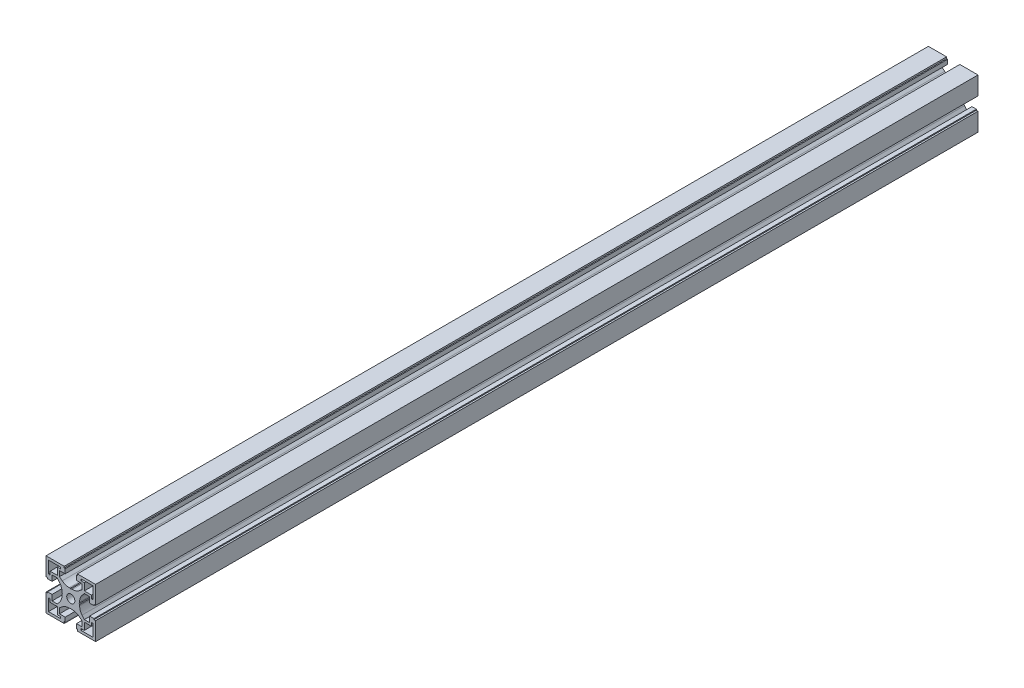
SolidWorks part; units mm, degrees
material "6061 Alloy"
ref_plane "Front Plane" through (0, 0, 0) normal (0, 0, 1) x (1, 0, 0)
ref_plane "Top Plane" through (0, 0, 0) normal (0, 1, 0) x (1, 0, 0)
ref_plane "Right Plane" through (0, 0, 0) normal (1, 0, 0) x (0, 0, -1)
sketch "Model" plane through (0, 0, 0) normal (0, 0, 1) x (1, 0, 0)
  line L0 (20.25, -9.25) -> (20.25, -20.25)
  line L1 (20.25, -9.25) -> (18.75, -9.25)
  line L2 (18.75, -9.25) -> (18.75, -12.25)
  line L3 (18.75, -12.25) -> (12.25, -12.25)
  line L4 (12.25, -12.25) -> (12.25, -18.75)
  line L5 (12.25, -18.75) -> (9.25, -18.75)
  line L6 (9.25, -18.75) -> (9.25, -20.25)
  line L7 (20.25, -20.25) -> (9.25, -20.25)
  line L8 (9.25, 20.25) -> (20.25, 20.25)
  line L9 (9.25, 20.25) -> (9.25, 18.75)
  line L10 (9.25, 18.75) -> (12.25, 18.75)
  line L11 (12.25, 18.75) -> (12.25, 12.25)
  line L12 (12.25, 12.25) -> (18.75, 12.25)
  line L13 (18.75, 12.25) -> (18.75, 9.25)
  line L14 (18.75, 9.25) -> (20.25, 9.25)
  line L15 (20.25, 20.25) -> (20.25, 9.25)
  line L16 (-9.25, -20.25) -> (-20.25, -20.25)
  line L17 (-9.25, -20.25) -> (-9.25, -18.75)
  line L18 (-9.25, -18.75) -> (-12.25, -18.75)
  line L19 (-12.25, -18.75) -> (-12.25, -12.25)
  line L20 (-12.25, -12.25) -> (-18.75, -12.25)
  line L21 (-18.75, -12.25) -> (-18.75, -9.25)
  line L22 (-18.75, -9.25) -> (-20.25, -9.25)
  line L23 (-20.25, -20.25) -> (-20.25, -9.25)
  line L24 (-20.25, 20.25) -> (-9.25, 20.25)
  line L25 (-20.25, 9.25) -> (-20.25, 20.25)
  line L26 (-20.25, 9.25) -> (-18.75, 9.25)
  line L27 (-18.75, 9.25) -> (-18.75, 12.25)
  line L28 (-18.75, 12.25) -> (-12.25, 12.25)
  line L29 (-12.25, 12.25) -> (-12.25, 18.75)
  line L30 (-12.25, 18.75) -> (-9.25, 18.75)
  line L31 (-9.25, 18.75) -> (-9.25, 20.25)
  line L32 (0.5, 8) -> (1.4727, 8)
  line L33 (7.7467, 10.213) -> (10.25, 12.2299)
  line L34 (10.25, 12.2299) -> (10.25, 17)
  line L35 (10.25, 17) -> (5.1, 17)
  line L36 (5.1, 17) -> (5.1, 21)
  line L37 (5.1, 21) -> (6, 21)
  line L38 (6, 22.5) -> (6, 21)
  line L39 (22.5, 22.5) -> (6, 22.5)
  line L40 (22.5, 6) -> (22.5, 22.5)
  line L41 (22.5, 6) -> (21, 6)
  line L42 (21, 6) -> (21, 5.1)
  line L43 (21, 5.1) -> (17, 5.1)
  line L44 (17, 5.1) -> (17, 10.25)
  line L45 (17, 10.25) -> (12.2299, 10.25)
  line L46 (12.2299, 10.25) -> (10.213, 7.7467)
  line L47 (8, 1.4727) -> (8, 0.5)
  line L48 (8, 0.5) -> (7.5, 0)
  line L49 (7.5, 0) -> (8, -0.5)
  line L50 (8, -0.5) -> (8, -1.4727)
  line L51 (10.213, -7.7467) -> (12.2299, -10.25)
  line L52 (12.2299, -10.25) -> (17, -10.25)
  line L53 (17, -10.25) -> (17, -5.1)
  line L54 (17, -5.1) -> (21, -5.1)
  line L55 (21, -5.1) -> (21, -6)
  line L56 (22.5, -6) -> (21, -6)
  line L57 (22.5, -22.5) -> (22.5, -6)
  line L58 (6, -22.5) -> (22.5, -22.5)
  line L59 (6, -22.5) -> (6, -21)
  line L60 (6, -21) -> (5.1, -21)
  line L61 (5.1, -21) -> (5.1, -17)
  line L62 (5.1, -17) -> (10.25, -17)
  line L63 (10.25, -17) -> (10.25, -12.2299)
  line L64 (10.25, -12.2299) -> (7.7467, -10.213)
  line L65 (1.4727, -8) -> (0.5, -8)
  line L66 (0.5, -8) -> (0, -7.5)
  line L67 (0, -7.5) -> (-0.5, -8)
  line L68 (-0.5, -8) -> (-1.4727, -8)
  line L69 (-7.7467, -10.213) -> (-10.25, -12.2299)
  line L70 (-10.25, -12.2299) -> (-10.25, -17)
  line L71 (-10.25, -17) -> (-5.1, -17)
  line L72 (-5.1, -17) -> (-5.1, -21)
  line L73 (-5.1, -21) -> (-6, -21)
  line L74 (-6, -22.5) -> (-6, -21)
  line L75 (-22.5, -22.5) -> (-6, -22.5)
  line L76 (-22.5, -6) -> (-22.5, -22.5)
  line L77 (-22.5, -6) -> (-21, -6)
  line L78 (-21, -6) -> (-21, -5.1)
  line L79 (-21, -5.1) -> (-17, -5.1)
  line L80 (-17, -5.1) -> (-17, -10.25)
  line L81 (-17, -10.25) -> (-12.2299, -10.25)
  line L82 (-12.2299, -10.25) -> (-10.213, -7.7467)
  line L83 (-8, -1.4727) -> (-8, -0.5)
  line L84 (-8, -0.5) -> (-7.5, 0)
  line L85 (-7.5, 0) -> (-8, 0.5)
  line L86 (-8, 0.5) -> (-8, 1.4727)
  line L87 (-10.213, 7.7467) -> (-12.2299, 10.25)
  line L88 (-12.2299, 10.25) -> (-17, 10.25)
  line L89 (-17, 10.25) -> (-17, 5.1)
  line L90 (-17, 5.1) -> (-21, 5.1)
  line L91 (-21, 5.1) -> (-21, 6)
  line L92 (-22.5, 6) -> (-21, 6)
  line L93 (-22.5, 22.5) -> (-22.5, 6)
  line L94 (-6, 22.5) -> (-22.5, 22.5)
  line L95 (-6, 22.5) -> (-6, 21)
  line L96 (-6, 21) -> (-5.1, 21)
  line L97 (-5.1, 21) -> (-5.1, 17)
  line L98 (-5.1, 17) -> (-10.25, 17)
  line L99 (-10.25, 17) -> (-10.25, 12.2299)
  line L100 (-10.25, 12.2299) -> (-7.7467, 10.213)
  line L101 (-1.4727, 8) -> (-0.5, 8)
  line L102 (-0.5, 8) -> (0, 7.5)
  line L103 (0, 7.5) -> (0.5, 8)
  arc A0 (1.4727, 8) -> (7.7467, 10.213) centre (1.4727, 18) ccw
  arc A1 (10.213, 7.7467) -> (8, 1.4727) centre (18, 1.4727) ccw
  arc A2 (8, -1.4727) -> (10.213, -7.7467) centre (18, -1.4727) ccw
  arc A3 (7.7467, -10.213) -> (1.4727, -8) centre (1.4727, -18) ccw
  arc A4 (-1.4727, -8) -> (-7.7467, -10.213) centre (-1.4727, -18) ccw
  arc A5 (-10.213, -7.7467) -> (-8, -1.4727) centre (-18, -1.4727) ccw
  arc A6 (-7.7467, 10.213) -> (-1.4727, 8) centre (-1.4727, 18) ccw
  circle A7 centre (0, 0) radius 3.7
  arc A8 (-8, 1.4727) -> (-10.213, 7.7467) centre (-18, 1.4727) ccw
  dimension "Vijak_diametar" = 7.4
extrude "Boss-Extrude1" add sketch "Model" against normal blind 800.5
equation "\"Lx_Alu_Profile_45x45H_Tuli\"= 800.5"
equation "\"LX_extrude2@Boss-Extrude1\"=\"Lx_Alu_Profile_45x45H_Tuli\""
